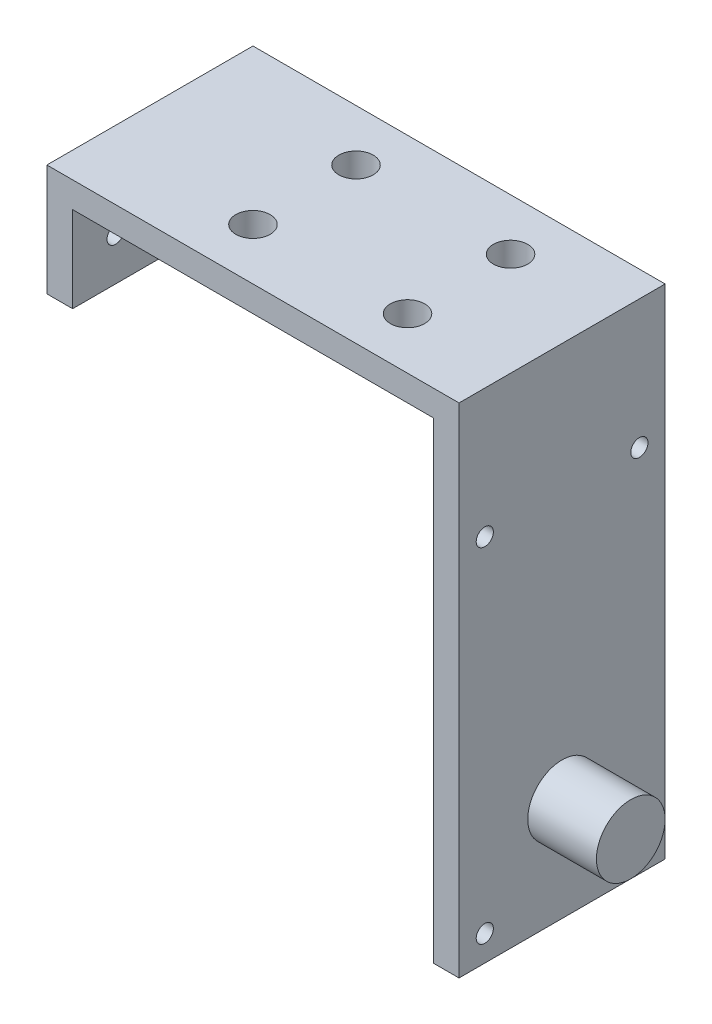
SolidWorks part; units mm, degrees
ref_plane "Front Plane" through (0, 0, 0) normal (0, 0, 1) x (1, 0, 0)
ref_plane "Top Plane" through (0, 0, 0) normal (0, 1, 0) x (1, 0, 0)
ref_plane "Right Plane" through (0, 0, 0) normal (1, 0, 0) x (0, 0, -1)
sketch "Sketch1" plane through (0, 0, 0) normal (0, 0, 1) x (1, 0, 0)
  line L0 (-10.5, 13) -> (10.5, 13)
  line L1 (-12, 14.5) -> (12, 14.5)
  line L2 (-12, 14.5) -> (-12, -14.5)
  line L3 (-12, -14.5) -> (12, -14.5)
  line L4 (12, 14.5) -> (12, -14.5)
  line L5 (-12, 14.5) -> (12, -14.5) construction
  line L6 (-12, -14.5) -> (12, 14.5) construction
  line L7 (10.5, 13) -> (10.5, -13)
  line L8 (-10.5, -13) -> (10.5, -13)
  line L9 (-10.5, 13) -> (-10.5, -13)
  point P0 (0, 0)
  dimension "D1" = 29
  dimension "D2" = 24
  dimension "D3" = 1.5
extrude "Boss-Extrude1" add sketch "Sketch1" along normal blind 12
sketch "Sketch2" plane through (0, -13, 0) normal (0, 1, 0) x (1, 0, 0)
  line L1 (-10.5, 0) -> (10.5, 0)
  line L2 (-10.5, 0) -> (-10.5, -12)
  line L3 (-10.5, -12) -> (10.5, -12)
  line L4 (10.5, 0) -> (10.5, -12)
extrude "Cut-Extrude1" cut sketch "Sketch2" against normal through all
sketch "Sketch4" plane through (-12, 0, 0) normal (-1, 0, 0) x (0, 0, 1)
  line L0 (12, 14.5) -> (12, -14.5) construction
  line L1 (0, -14.5) -> (12, -14.5)
  line L2 (0, -14.5) -> (0, 8)
  line L3 (0, 8) -> (12, 8)
  line L4 (12, -14.5) -> (12, 8)
  line L5 (12, 14.5) -> (0, 14.5) construction
  dimension "D1" = 6.5
extrude "Cut-Extrude2" cut sketch "Sketch4" against normal blind 12
sketch "Sketch5" plane through (12, 0, 0) normal (1, 0, 0) x (0, 0, -1)
  line L0 (-12, -14.5) -> (0, -14.5) construction
  line L1 (-12, -14.5) -> (-12, 14.5) construction
  line L2 (-6, -14.5) -> (-6, 17.1239) construction
  circle A0 centre (-10.5, -13) radius 0.5
  circle A1 centre (-1.5, -13) radius 0.5
  circle A2 centre (-10.5, 7) radius 0.5
  circle A3 centre (-1.5, 7) radius 0.5
  dimension "D1" = 1.5
  dimension "D2" = 1.5
  dimension "D3" = 2
extrude "Cut-Extrude3" cut sketch "Sketch5" against normal blind 12
sketch "Sketch6" plane through (-12, 0, 0) normal (-1, 0, 0) x (0, 0, 1)
  line L0 (12, 8) -> (0, 8) construction
  line L1 (12, 14.5) -> (12, 8) construction
  line L2 (6, 14.5) -> (6, 6.7125) construction
  line L3 (12, 14.5) -> (0, 14.5) construction
  circle A0 centre (9.5, 10.5) radius 0.5
  circle A1 centre (2.5, 10.5) radius 0.5
  dimension "D1" = 2.5
  dimension "D2" = 2.5
extrude "Cut-Extrude4" cut sketch "Sketch6" against normal blind 12
sketch "Sketch7" plane through (12, 0, 0) normal (1, 0, 0) x (0, 0, -1)
  line L0 (-6, -14.5) -> (-6, 15.9965) construction
  line L1 (-12, -14.5) -> (0, -14.5) construction
  circle A0 centre (-6, -8.5) radius 2
  dimension "D1" = 6
extrude "Boss-Extrude2" add sketch "Sketch7" along normal blind 4
sketch "Sketch9" plane through (0, 14.5, 0) normal (0, 1, 0) x (1, 0, 0)
  line L0 (12, -6) -> (-12, -6) construction
  line L1 (12, -12) -> (12, 0) construction
  line L2 (-12, -12) -> (-12, 0) construction
  circle A0 centre (6, -3) radius 1
  circle A1 centre (6, -9) radius 1
  circle A2 centre (-3, -3) radius 1
  circle A3 centre (-3, -9) radius 1
  dimension "D1" = 6
  dimension "D2" = 3
  dimension "D4" = 9
  dimension "D3" = 2
extrude "Cut-Extrude5" cut sketch "Sketch9" against normal blind 10
